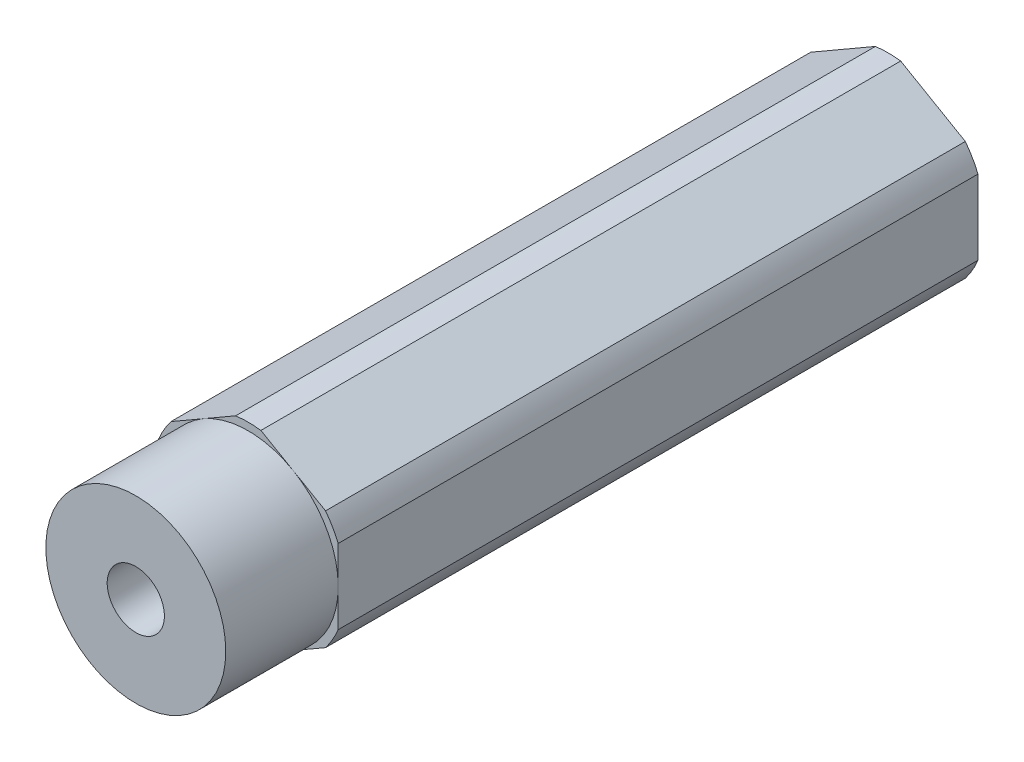
SolidWorks part; units mm, degrees
material "7075-T6 (SN)"
ref_plane "Front Plane" through (0, 0, 0) normal (0, 0, 1) x (1, 0, 0)
ref_plane "Top Plane" through (0, 0, 0) normal (0, 1, 0) x (1, 0, 0)
ref_plane "Right Plane" through (0, 0, 0) normal (1, 0, 0) x (0, 0, -1)
sketch "Sketch1" plane through (0, 0, 0) normal (0, 0, 1) x (1, 0, 0)
  line L1 (0, 7.3323) -> (-6.35, 3.6662)
  line L2 (-6.35, 3.6662) -> (-6.35, -3.6662)
  line L3 (-6.35, -3.6662) -> (0, -7.3323)
  line L4 (0, -7.3323) -> (6.35, -3.6662)
  line L5 (6.35, -3.6662) -> (6.35, 3.6662)
  line L6 (6.35, 3.6662) -> (0, 7.3323)
  circle A0 centre (0, 0) radius 6.35 construction
  circle A1 centre (0, 0) radius 6.875
  circle A2 centre (0, 0) radius 2.0193
  dimension "D1" = 12.7
  dimension "D2" = 4.0386
  dimension "D3" = 13.75
extrude "Boss-Extrude1" add sketch "Sketch1" along normal mid plane 53.1 contours L5 A1 L6 L1 L2 L3 L4 A2
hole_wizard "#10-32 Tapped Hole1" positions "3DSketch2" profile "Sketch3" tap size "#10-32" standard "ANSI Inch"
sketch3d "3DSketch2"
  circle A0 centre (0, 0, -26.55) radius 2.0193 construction
  circle A1 centre (0, 0, 26.55) radius 2.0193 construction
  point P0 (0, 0, 26.55)
  point P2 (0, 0, -26.55)
  point P7 (0, 0, -24.5307)
  point P10 (0, 0, 28.5693)
sketch "Sketch3" plane through (0, 0, 26.55) normal (1, 0, 0) x (0, -1, 0)
  line L0 (0, 0) -> (0, 13.2428)
  line L1 (0, 13.2428) -> (2.0193, 12.0294)
  line L2 (2.0193, 12.0294) -> (2.0193, 0)
  line L5 (2.0193, 0) -> (0, 0)
  line L10 (0, 13.2428) -> (-2.0193, 12.0294) construction
  line L11 (0, -6.35) -> (0, 107.95) construction
  dimension "Tap Drill Dia." = 4.0386
  dimension "Tap Drill Depth" = 12.0294
  dimension "Drill Angle" = 118
cosmetic thread "Hole Thread1" parameters "D1"=9.652, "D2"=4.826
cosmetic thread "Hole Thread2" parameters "D1"=9.652, "D2"=4.826
sketch "Sketch5" plane through (0, 0, 26.55) normal (0, 0, 1) x (1, 0, 0)
  circle A0 centre (0, 0) radius 6.875
  circle A1 centre (0, 0) radius 6.35
  arc A2 (0.893, 6.8168) -> (-0.893, 6.8168) centre (0, 0) ccw construction
  dimension "D1" = 12.7
extrude "Cut-Extrude1" cut sketch "Sketch5" against normal blind 7.9375
equation "\"D3@Sketch1\"=13.75mm"
